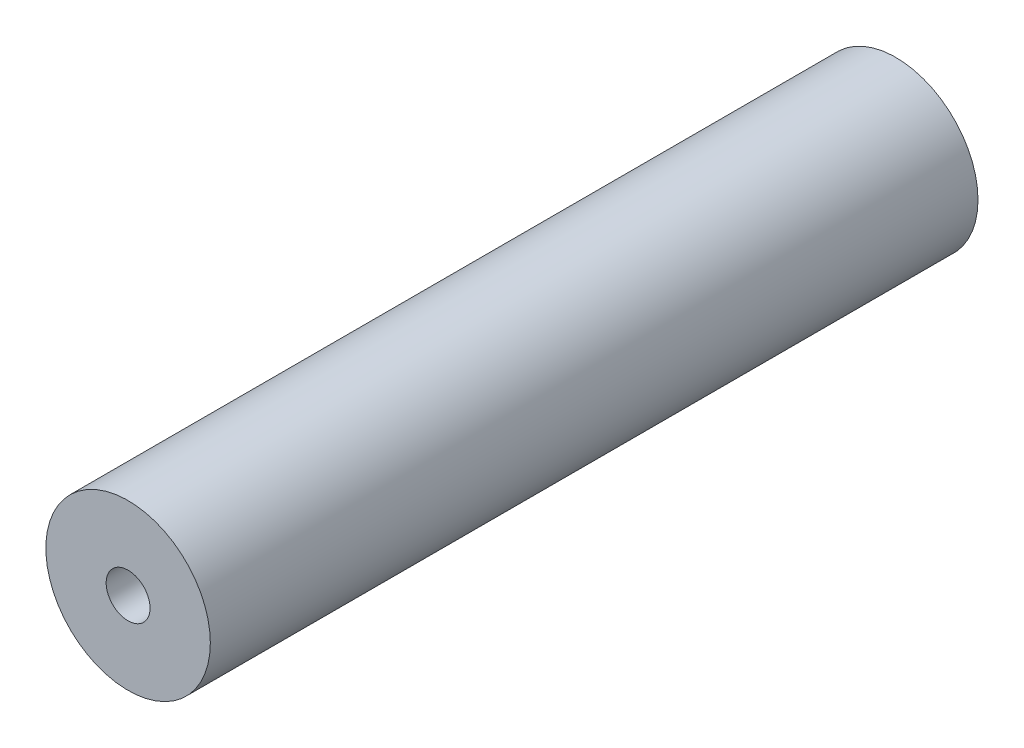
SolidWorks part; units mm, degrees
material "ABS"
ref_plane "Front Plane" through (0, 0, 0) normal (0, 0, 1) x (1, 0, 0)
ref_plane "Top Plane" through (0, 0, 0) normal (0, 1, 0) x (1, 0, 0)
ref_plane "Right Plane" through (0, 0, 0) normal (1, 0, 0) x (0, 0, -1)
sketch "Sketch1" plane through (0, 0, 0) normal (0, 0, 1) x (1, 0, 0)
  circle A0 centre (0, 0) radius 4.7625
  circle A1 centre (0, 0) radius 1.27
  dimension "D1" = 9.525
  dimension "D2" = 2.54
extrude "Boss-Extrude1" add sketch "Sketch1" along normal blind 44.45
